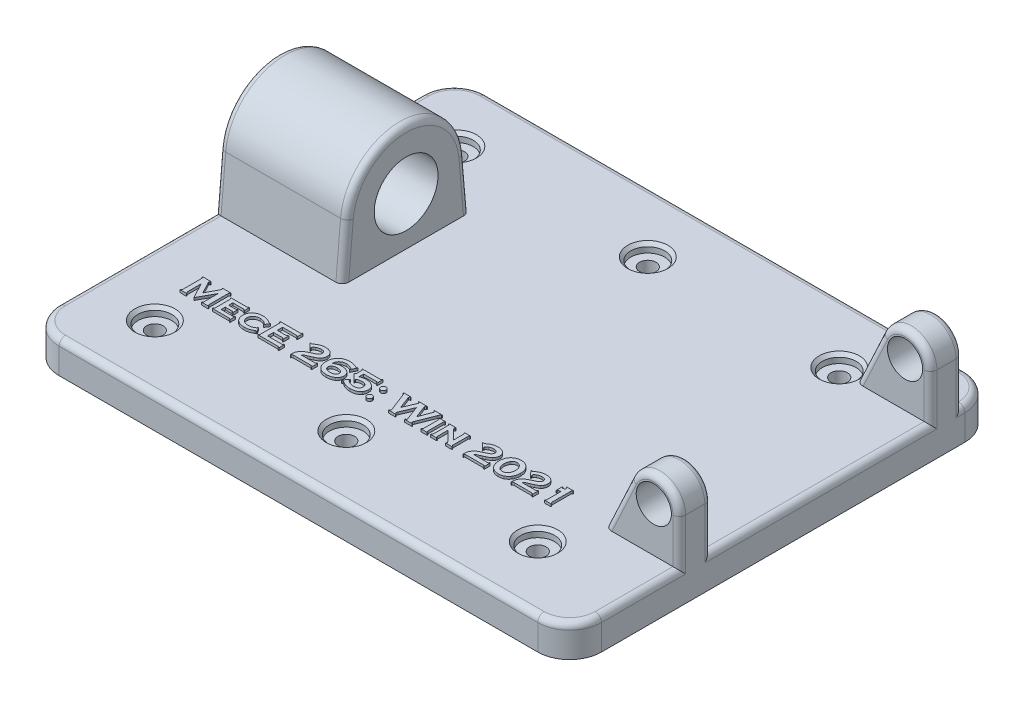
SolidWorks part; units mm, degrees
material "Gray Cast Iron (SN)"
ref_plane "Front" through (0, 0, 0) normal (0, 0, 1) x (1, 0, 0)
ref_plane "Top" through (0, 0, 0) normal (0, 1, 0) x (1, 0, 0)
ref_plane "Right" through (0, 0, 0) normal (1, 0, 0) x (0, 0, -1)
ref_plane "Plane S1" through (0, 0, 25) normal (0, 0, 1) x (1, 0, 0)
sketch "Sketch1" plane through (0, 0, 0) normal (0, 0, 1) x (1, 0, 0)
  line L0 (0, 0) -> (107.95, 0)
  line L1 (0, 0) -> (0, 6.35)
  line L2 (107.95, 6.35) -> (0, 6.35)
  line L3 (107.95, 6.35) -> (107.95, 0)
  dimension "D1" = 107.95
  dimension "D2" = 6.35
extrude "Base-Extrude" add sketch "Sketch1" along normal blind 50 and the other way blind 35
sketch "Sketch2" plane through (0, 0, 25) normal (0, 0, 1) x (1, 0, 0)
  line L0 (107.95, 6.35) -> (107.95, 15.24)
  line L1 (98.266, 17.3869) -> (93.1194, 6.35)
  line L2 (107.95, 6.35) -> (0, 6.35) construction
  line L3 (93.1194, 6.35) -> (107.95, 6.35)
  line L4 (0, 0) -> (107.95, 0) construction
  arc A0 (107.95, 15.24) -> (98.266, 17.3869) centre (102.87, 15.24) ccw
  dimension "D1" = 5.08
  dimension "D2" = 15.24
  dimension "D3" = 65
extrude "Lever boss" add sketch "Sketch2" along normal mid plane 6.35
fillet "Base Corner Fillet" radius 6.35 4 edges at (107.95, 3.175, 50) (0, 3.175, -35) (107.95, 3.175, -35) (0, 3.175, 50)
sketch "Sketch3" plane through (0, 0, 0) normal (-1, 0, 0) x (0, 0, 1)
  line L0 (0, 0) -> (0, 31.6598) construction
  line L1 (12.7, 6.35) -> (11.7765, 16.9053)
  line L2 (43.65, 6.35) -> (-28.65, 6.35) construction
  line L3 (-12.7, 6.35) -> (-11.7765, 16.9053)
  line L4 (-12.7, 6.35) -> (12.7, 6.35)
  arc A0 (-11.7765, 16.9053) -> (11.7765, 16.9053) centre (0, 15.875) cw
  dimension "D2" = 9.525
  dimension "D1" = 25.4
  dimension "D3" = 85
extrude "Plunger-Boss-Extrude" add sketch "Sketch3" against normal blind 25.4
hole_wizard "Plunger-Hole" positions "Sketch6" profile "Sketch7" legacy end condition through all
sketch "Sketch6" plane through (25.4, 3.19, 95.1751) normal (1, 0, 0) x (0, 0, -1)
  arc A1 (106.9516, 13.7153) -> (83.3985, 13.7153) centre (95.1751, 12.685) ccw construction
  point P0 (95.1751, 12.685)
sketch "Sketch7" plane through (25.4, 15.875, 0) normal (0, 1, 0) x (0, 0, -1)
  line L0 (0, 0) -> (0, 25.4)
  line L1 (0, 25.4) -> (6.35, 25.4)
  line L2 (6.35, 25.4) -> (6.35, 0)
  line L3 (6.35, 0) -> (0, 0)
  line L4 (0, 110) -> (0, -10) construction
  dimension "Diameter" = 12.7
  dimension "Depth" = 25.4
sketch "Sketch8" plane through (72.2885, 6.35, 6.6308) normal (0, 1, 0) x (-1, 0, 0)
  line L0 (-29.3115, 43.3692) -> (65.9385, 43.3692) construction
  line L1 (-35.6615, 37.0192) -> (-35.6615, 21.5442) construction
  point P0 (-16.6115, 30.6692)
  dimension "D1" = 12.7
  dimension "D2" = 19.05
sketch "Sketch9" plane through (88.9, 6.35, 22.3) normal (1, 0, 0) x (0, 0, 1)
  line L0 (0, 0) -> (0, 6.35)
  line L1 (0, 6.35) -> (1.8034, 6.35)
  line L2 (1.8034, 6.35) -> (1.8034, 0.762)
  line L3 (1.8034, 0.762) -> (3.175, 0.762)
  line L4 (3.175, 0.762) -> (3.175, 0)
  line L5 (3.175, 0) -> (0, 0)
  line L6 (0, 17.8287) -> (0, -10) construction
  dimension "Diameter" = 3.6068
  dimension "Depth" = 6.35
  dimension "C-Bore Diameter" = 6.35
  dimension "C-Bore Depth" = 0.762
hole_wizard "CBORE for #4 Binding Head Machine Screw1" positions "Sketch8" profile "Sketch9" counterbore size "#4" standard "Ansi Inch" end condition through all
sketch "Sketch9" plane through (88.9, 6.35, 37.3) normal (1, 0, 0) x (0, 0, 1)
  line L0 (0, 0) -> (0, 6.35)
  line L1 (0, 6.35) -> (1.6319, 6.35)
  line L3 (1.6319, 6.35) -> (1.6319, 1.7272)
  line L4 (3.3731, 1.7272) -> (1.6319, 1.7272)
  line L5 (3.3731, 1.7272) -> (3.3731, 0.635)
  line L6 (3.3731, 0.635) -> (4.0081, 0)
  line L7 (4.0081, 0) -> (0, 0)
  line L8 (-3.3731, 0.635) -> (-4.0081, 0) construction
  line L11 (0, -6.35) -> (0, 107.95) construction
  dimension "Thru Hole Dia." = 3.2639
  dimension "Thru Hole Depth" = 6.35
  dimension "C'Bore Dia." = 6.7462
  dimension "C'Bore Depth" = 1.7272
  dimension "Near C'Sink Dia." = 8.0162
  dimension "Near C'Sink Angle" = 90
pattern_linear "LPattern1" count 3 spacing 38.1 along (-1, 0, 0) count 2 spacing 60 along (0, 0, -1) of "CBORE for #4 Binding Head Machine Screw1"
hole_wizard "Lever Boss Hole" positions "Sketch5" profile "Sketch4" hole size "Ø6.0" standard "Ansi Metric" end condition through all
sketch "Sketch5" plane through (0, 0, 28.175) normal (0, 0, 1) x (1, 0, 0)
  arc A0 (107.95, 15.24) -> (98.266, 17.3869) centre (102.87, 15.24) ccw construction
  point P0 (102.87, 15.24)
sketch "Sketch4" plane through (102.87, 15.24, 28.175) normal (1, 0, 0) x (0, -1, 0)
  line L0 (0, 0) -> (0, 78.175)
  line L1 (0, 78.175) -> (3.5, 78.175)
  line L2 (3.5, 78.175) -> (3.5, 0)
  line L5 (3.5, 0) -> (0, 0)
  line L11 (0, -6.35) -> (0, 107.95) construction
  dimension "Thru Hole Dia." = 7
  dimension "Thru Hole Depth" = 78.175
mirror "Mirror1" about plane through (0, 0, 0) normal (0, 0, 1) of "Lever boss", "Lever Boss Hole"
fillet "Lever Boss Fillet" radius 1.27 12 edges at (95.6927, 11.8685, -28.175) (103.9695, 20.1996, -28.175) (107.95, 10.795, -28.175) (107.95, 10.795, -21.825) (103.9695, 20.1996, -21.825) (95.6927, 11.8685, -21.825) (107.95, 10.795, 21.825) (103.9695, 20.1996, 21.825) (95.6927, 11.8685, 21.825) (107.95, 10.795, 28.175) (103.9695, 20.1996, 28.175) (95.6927, 11.8685, 28.175)
fillet "Base Fillet" radius 1.27 21 edges at (107.95, 6.35, -27.7775) (107.578, 6.35, 27.803) (107.578, 6.35, -27.803) (107.578, 6.35, -22.197) (107.578, 6.35, 22.197) (107.95, 6.35, 0) (53.975, 6.35, -35) (0, 6.35, 28.175) (53.975, 6.35, 50) (107.95, 6.35, 35.2775) (106.0901, 6.35, -33.1401) (106.0901, 6.35, 48.1401) (1.8599, 6.35, 48.1401) (1.8599, 6.35, -33.1401) (0, 6.35, -20.675) (0, 11.6277, -12.2383) (0, 27.6965, 0) (25.4, 11.6277, 12.2383) (25.4, 11.6277, -12.2383) (25.4, 27.6965, 0) (0, 11.6277, 12.2383)
sketch "Sketch10" plane through (0, 6.35, 0) normal (0, 1, 0) x (1, 0, 0)
  line L1 (20.7309, 40.5268) -> (30.6341, 40.5268)
  line L2 (20.7309, 40.5268) -> (20.7309, 30.859)
  line L3 (20.7309, 30.859) -> (30.6341, 30.859)
  line L4 (30.6341, 40.5268) -> (30.6341, 30.859)
  line L5 (20.7309, 40.5268) -> (30.6341, 30.859) construction
  line L6 (20.7309, 30.859) -> (30.6341, 40.5268) construction
  point P0 (25.6825, 35.6929)
extrude "Boss-Extrude3" [suppressed] add sketch "Sketch10" along normal blind 10
sketch "Sketch11" plane through (0, 6.35, 0) normal (0, 1, 0) x (1, 0, 0)
  line L0 (10, -30) -> (95.746, -30) construction
  line L1 (6.35, 35) -> (101.6, 35) construction
  line L2 (0, 11.5363) -> (0, 28.65) construction
  text T0 "MecE 265: Win 2021" font "Copperplate Gothic Bold" height in points 22
  dimension "D1" = 65
  dimension "D2" = 10
extrude "NamePlate" add sketch "Sketch11" along normal blind 0.5
